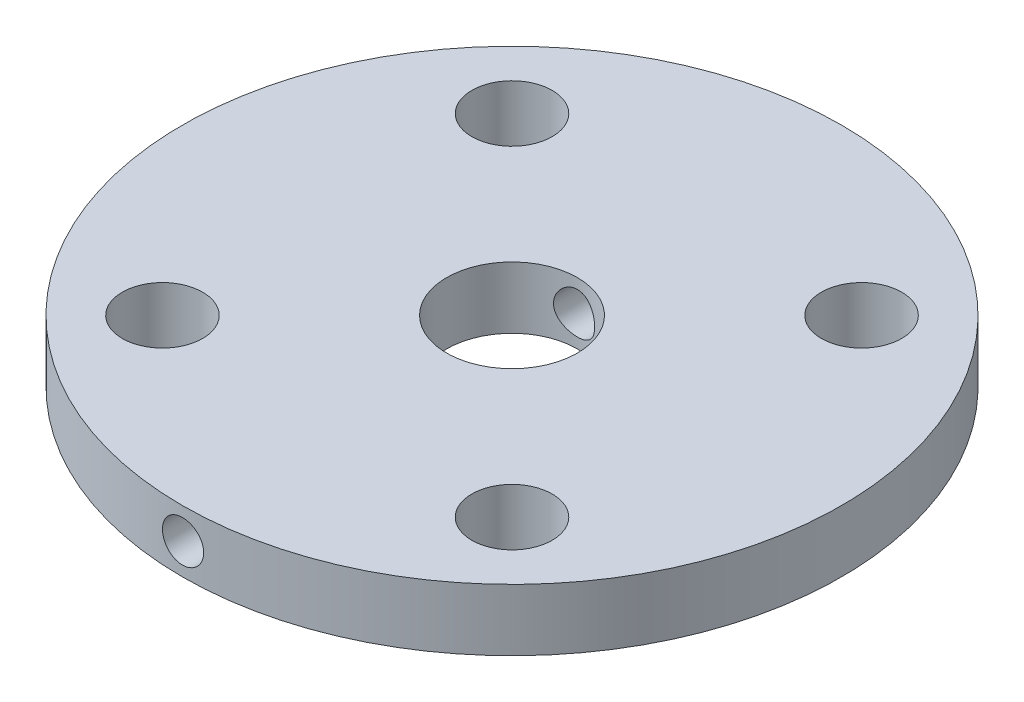
SolidWorks part; units mm, degrees
ref_plane "Front Plane" through (0, 0, 0) normal (0, 0, 1) x (1, 0, 0)
ref_plane "Top Plane" through (0, 0, 0) normal (0, 1, 0) x (1, 0, 0)
ref_plane "Right Plane" through (0, 0, 0) normal (1, 0, 0) x (0, 0, -1)
sketch "Sketch1" plane through (0, 0, 0) normal (0, 1, 0) x (1, 0, 0)
  line L1 (-16, -16) -> (16, -16)
  line L2 (-16, -16) -> (-16, 16)
  line L3 (-16, 16) -> (16, 16)
  line L4 (16, -16) -> (16, 16)
  line L5 (-16, -16) -> (16, 16) construction
  line L6 (-16, 16) -> (16, -16) construction
  circle A0 centre (0, 0) radius 16
  circle A1 centre (0, 0) radius 8
  dimension "D1" = 32
  dimension "D2" = 16
extrude "Boss-Extrude1" add sketch "Sketch1" along normal blind 3 contours A0 A1
sketch "Sketch2" plane through (0, 3, 0) normal (0, 1, 0) x (1, 0, 0)
  line L1 (-16, -16) -> (16, -16)
  line L2 (-16, -16) -> (-16, 16)
  line L3 (-16, 16) -> (16, 16)
  line L4 (16, -16) -> (16, 16)
  line L5 (-16, -16) -> (16, 16) construction
  line L6 (-16, 16) -> (16, -16) construction
  line L7 (-5.8336, 11.1369) -> (-11.1369, 5.8336) construction
  circle A0 centre (0, 0) radius 16 construction
  point P0 (0, 0)
  point P15 (-8.4853, 8.4853)
  point P18 (8.4853, 8.4853)
  point P19 (8.4853, -8.4853)
  point P20 (-8.4853, -8.4853)
  dimension "D2" = 12
  dimension "D3" = 7.5
  dimension "D5" = 12
  dimension "D4" = 4
hole_wizard "Ø3.0mm Dowel Hole1" positions "3DSketch1" profile "Sketch12" hole size "Ø3.0" standard "ANSI Metric" end condition through all
sketch3d "3DSketch1"
  point P0 (8.4853, 3, 8.4853)
  point P3 (-8.4853, 3, 8.4853)
  point P6 (-8.4853, 3, -8.4853)
  point P9 (8.4853, 3, -8.4853)
sketch "Sketch12" plane through (8.4853, 3, 8.4853) normal (1, 0, 0) x (0, 0, 1)
  line L0 (0, 0) -> (0, 3)
  line L1 (0, 3) -> (1.95, 3)
  line L2 (1.95, 3) -> (1.95, 0)
  line L5 (1.95, 0) -> (0, 0)
  line L11 (0, -6.35) -> (0, 107.95) construction
  dimension "Thru Hole Dia." = 3.9
  dimension "Thru Hole Depth" = 3
sketch "Sketch6" plane through (0, 0, 0) normal (0, -1, 0) x (1, 0, 0)
  circle A1 centre (0, 0) radius 3.175
  circle A3 centre (0, 0) radius 6.175
  dimension "D2" = 6.35
  dimension "D1" = 3
extrude "Cut-Extrude3" cut sketch "Sketch6" against normal through all
ref_plane "Plane2" through (0, 0, 16) normal (0, 0, 1) x (1, 0, 0)
sketch "Sketch14" plane through (0, 0, 16) normal (0, 0, 1) x (1, 0, 0)
  line L0 (-16, 0) -> (16, 0) construction
  line L1 (0, 3) -> (0, 0) construction
  circle A1 centre (0, 1.5) radius 1
  dimension "D1" = 2
  dimension "D2" = 1.5
extrude "Cut-Extrude4" cut sketch "Sketch14" against normal blind 40 contours A1
ref_plane "Plane1" through (0, 0, 7) normal (0, 0, 1) x (1, 0, 0)
sketch "Sketch7" plane through (0, 0, 0) normal (0, 0, 1) x (1, 0, 0)
  circle A0 centre (0, -5) radius 1
  circle A1 centre (0, -5) radius 1.9
  point P10 (0, -5)
  dimension "D1" = 2
  dimension "D2" = 3.8
  dimension "D3" = 5
extrude "Cut-Extrude1" cut sketch "Sketch7" along normal blind 10.5 contours A0
sketch "Sketch11" plane through (0, 0, 7) normal (0, 0, 1) x (1, 0, 0)
  line L0 (0, 0) -> (0, -6.35)
  circle A0 centre (0, -5) radius 1.9
  dimension "D1" = 3.8
  dimension "D2" = 6.35
extrude "Cut-Extrude2" cut sketch "Sketch11" against normal blind 2 contours A0
